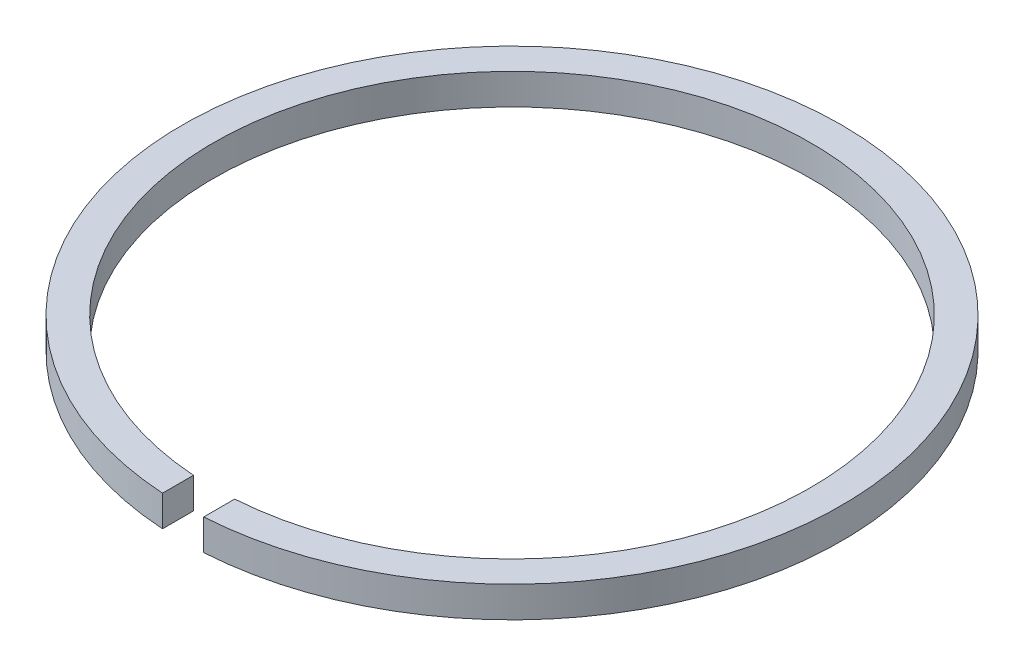
SolidWorks part; units mm, degrees
ref_plane "Front Plane" through (0, 0, 0) normal (0, 0, 1) x (1, 0, 0)
ref_plane "Top Plane" through (0, 0, 0) normal (0, 1, 0) x (1, 0, 0)
ref_plane "Right Plane" through (0, 0, 0) normal (1, 0, 0) x (0, 0, -1)
sketch "Sketch1" plane through (0, 0, 0) normal (0, 1, 0) x (1, 0, 0)
  line L0 (0, 0) -> (0, 20.8772) construction
  line L1 (-1, -14.4655) -> (-1, -15.9687)
  line L2 (1, -14.4655) -> (1, -15.9687)
  arc A0 (1, -15.9687) -> (-1, -15.9687) centre (0, 0) ccw
  arc A1 (1, -14.4655) -> (-1, -14.4655) centre (0, 0) ccw
  dimension "D1" = 32
  dimension "D2" = 29
  dimension "D3" = 2
  dimension "D4" = 1
extrude "Boss-Extrude1" add sketch "Sketch1" along normal mid plane 1.5
